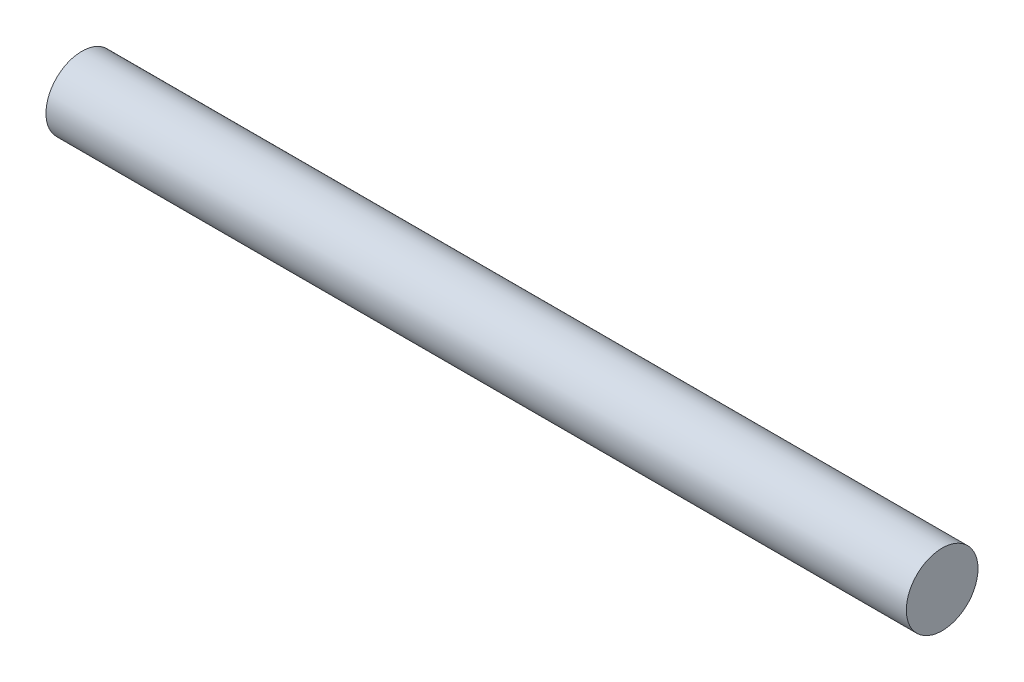
SolidWorks part; units mm, degrees
ref_plane "Front Plane" through (0, 0, 0) normal (0, 0, 1) x (1, 0, 0)
ref_plane "Top Plane" through (0, 0, 0) normal (0, 1, 0) x (1, 0, 0)
ref_plane "Right Plane" through (0, 0, 0) normal (1, 0, 0) x (0, 0, -1)
sketch "Sketch1" plane through (0, 0, 0) normal (1, 0, 0) x (0, 0, -1)
  circle A0 centre (0, 0) radius 2.5
extrude "Boss-Extrude1" add sketch "Sketch1" along normal mid plane 60
